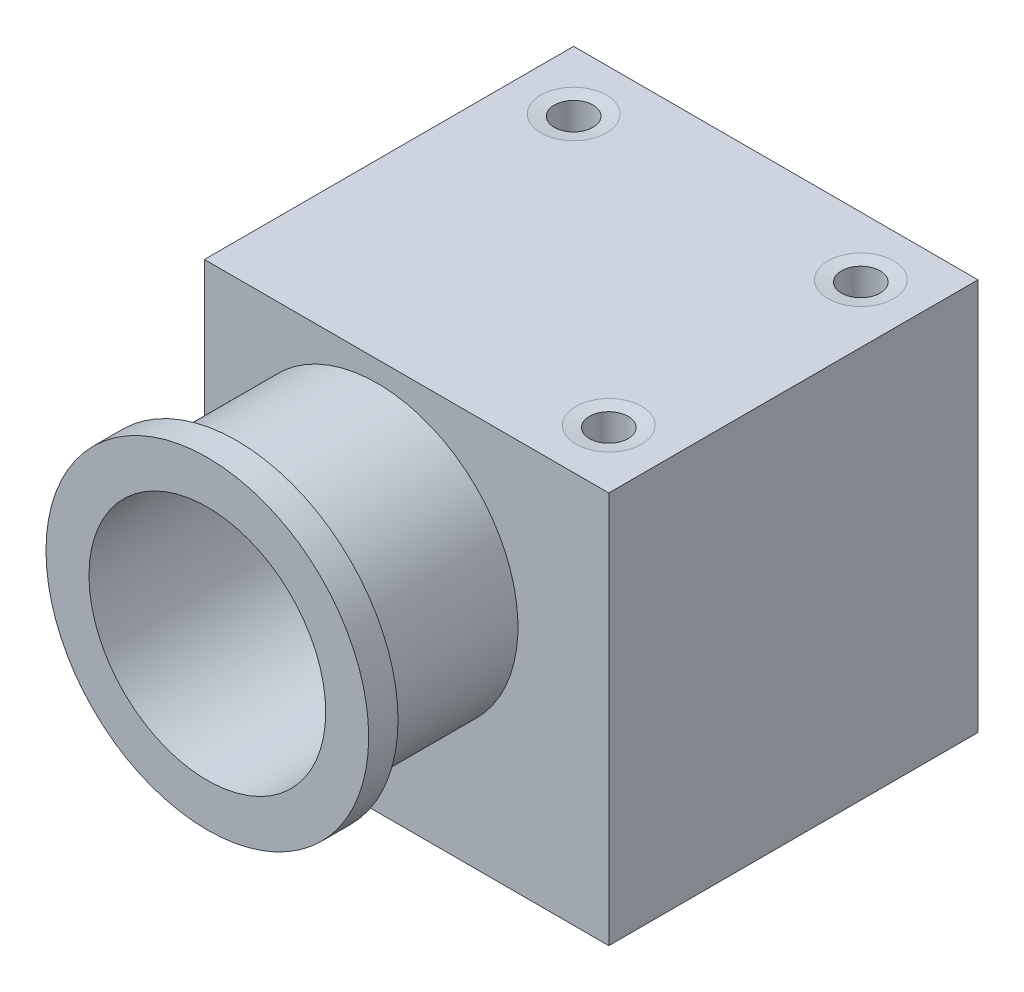
SolidWorks part; units mm, degrees
material "PTFE (general)"
ref_plane "Front Plane" through (0, 0, 0) normal (0, 0, 1) x (1, 0, 0)
ref_plane "Top Plane" through (0, 0, 0) normal (0, 1, 0) x (1, 0, 0)
ref_plane "Right Plane" through (0, 0, 0) normal (1, 0, 0) x (0, 0, -1)
sketch "Sketch1" plane through (0, 0, 0) normal (0, 0, 1) x (1, 0, 0)
  line L1 (-7.493, -8.4963) -> (7.493, -8.4963)
  line L2 (-7.493, -8.4963) -> (-7.493, 8.4963)
  line L3 (-7.493, 8.4963) -> (7.493, 8.4963)
  line L4 (7.493, -8.4963) -> (7.493, 8.4963)
  line L5 (-7.493, -8.4963) -> (7.493, 8.4963) construction
  line L6 (-7.493, 8.4963) -> (7.493, -8.4963) construction
  point P0 (0, 0)
  dimension "D1" = 14.986
  dimension "D2" = 16.9926
extrude "Boss-Extrude4" add sketch "Sketch1" against normal blind 24.1554 contours L3 L4 L1 L2
sketch "Sketch10" plane through (0, 0, 0) normal (0, 0, 1) x (1, 0, 0)
  circle A0 centre (0, 1.5037) radius 1.4224
  dimension "D1" = 2.8448
extrude "Cut-Extrude6" cut sketch "Sketch10" against normal blind 24.1554
sketch "Sketch11" plane through (0, 0, 0) normal (0, 0, 1) x (1, 0, 0)
  circle A0 centre (0, 1.5037) radius 3.2639
  dimension "D1" = 6.5278
extrude "Cut-Extrude7" cut sketch "Sketch11" against normal blind 19.558
sketch "Sketch12" plane through (0, 0, 0) normal (0, 0, 1) x (1, 0, 0)
  circle A0 centre (0, 1.5037) radius 5.1308
  dimension "D1" = 10.2616
extrude "Cut-Extrude8" cut sketch "Sketch12" against normal blind 18.288
sketch "Sketch13" plane through (0, 0, 0) normal (0, 0, 1) x (1, 0, 0)
  line L1 (-7.493, 8.4963) -> (7.493, 8.4963)
  line L2 (-7.493, 8.4963) -> (-7.493, -8.4963)
  line L3 (-7.493, -8.4963) -> (7.493, -8.4963)
  line L4 (7.493, 8.4963) -> (7.493, -8.4963)
  circle A0 centre (0, 1.5037) radius 5.1308
extrude "Cut-Extrude9" cut sketch "Sketch13" against normal blind 7.366
sketch "Sketch14" plane through (0, 0, -7.366) normal (0, 0, 1) x (1, 0, 0)
  circle A0 centre (0, 1.5037) radius 5.1308
  circle A1 centre (0, 1.5037) radius 6.096
  dimension "D1" = 12.192
extrude "Boss-Extrude5" add sketch "Sketch14" along normal blind 6.096
sketch "Sketch15" plane through (0, 0, -1.27) normal (0, 0, 1) x (1, 0, 0)
  circle A0 centre (0, 1.5037) radius 5.1308
  circle A1 centre (0, 1.5037) radius 6.9926
extrude "Boss-Extrude6" add sketch "Sketch15" along normal blind 1.27
sketch "Sketch16" plane through (0, 0, -24.1554) normal (0, 0, -1) x (-1, 0, 0)
  line L1 (7.493, -8.4963) -> (-7.493, -8.4963)
  line L2 (7.493, -8.4963) -> (7.493, 8.4963)
  line L3 (7.493, 8.4963) -> (-7.493, 8.4963)
  line L4 (-7.493, -8.4963) -> (-7.493, 8.4963)
extrude "Cut-Extrude10" cut sketch "Sketch16" against normal blind 0.7874
sketch "Sketch18" plane through (7.493, 0, 0) normal (1, 0, 0) x (0, 0, -1)
  line L1 (7.366, 8.4963) -> (23.368, 8.4963)
  line L2 (7.366, 8.4963) -> (7.366, -8.4963)
  line L3 (7.366, -8.4963) -> (23.368, -8.4963)
  line L4 (23.368, 8.4963) -> (23.368, -8.4963)
extrude "Boss-Extrude7" add sketch "Sketch18" along normal blind 2.54
sketch "Sketch19" plane through (0, 8.4963, 0) normal (0, 1, 0) x (1, 0, 0)
  line L0 (10.033, 7.366) -> (-7.493, 7.366) construction
  line L1 (10.033, 23.368) -> (10.033, 7.366) construction
  line L2 (-7.493, 23.368) -> (10.033, 23.368) construction
  line L3 (-7.493, 23.368) -> (-7.493, 7.366) construction
  circle A0 centre (-4.953, 20.828) radius 0.8382
  circle A1 centre (7.493, 20.828) radius 0.8382
  circle A2 centre (7.493, 9.906) radius 0.8382
  dimension "D1" = 1.6764
  dimension "D2" = 1.6764
  dimension "D3" = 1.6764
  dimension "D4" = 2.54
  dimension "D5" = 2.54
  dimension "D6" = 2.54
  dimension "D7" = 2.54
  dimension "D8" = 2.54
  dimension "D9" = 2.54
extrude "Cut-Extrude11" cut sketch "Sketch19" against normal blind 20.32
ref_plane "Plane2" through (0, 7.6073, 0) normal (0, 1, 0) x (1, 0, 0)
sketch "Sketch22" plane through (0, 8.4963, 0) normal (0, 1, 0) x (1, 0, 0)
  circle A0 centre (-4.953, 20.828) radius 1.4224
  circle A1 centre (7.493, 20.828) radius 1.4224
  circle A2 centre (7.493, 9.906) radius 1.4224
  dimension "D1" = 2.8448
  dimension "D2" = 2.8448
  dimension "D3" = 2.8448
extrude "Cut-Extrude13" cut sketch "Sketch22" against normal blind 0.889 draft 82
sketch "Sketch23" plane through (-7.493, 0, 0) normal (-1, 0, 0) x (0, 0, 1)
